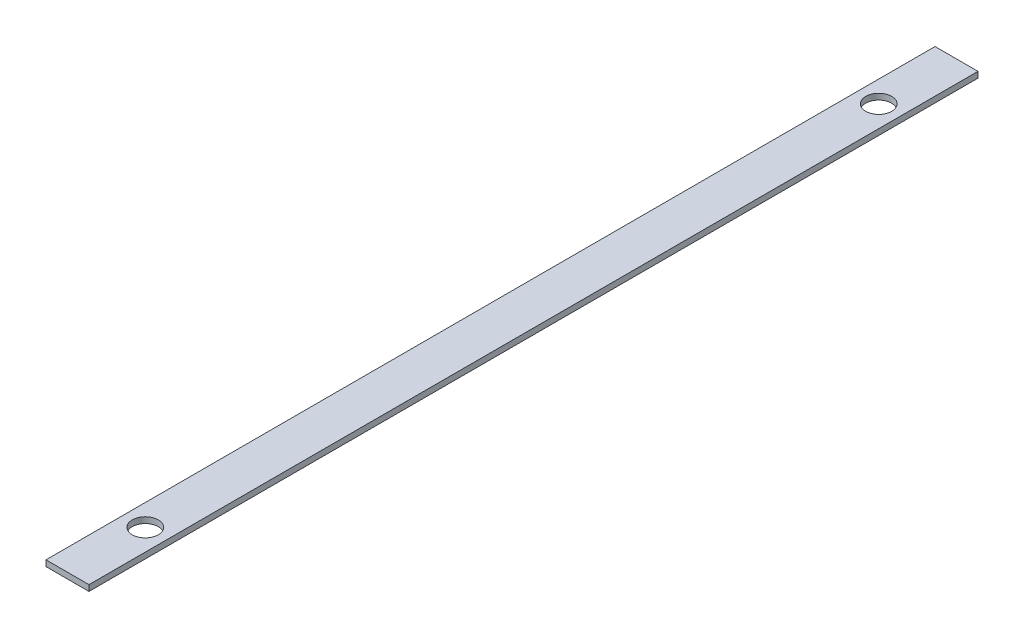
SolidWorks part; units mm, degrees
ref_plane "Front Plane" through (0, 0, 0) normal (0, 0, 1) x (1, 0, 0)
ref_plane "Top Plane" through (0, 0, 0) normal (0, 1, 0) x (1, 0, 0)
ref_plane "Right Plane" through (0, 0, 0) normal (1, 0, 0) x (0, 0, -1)
sketch "Sketch1" plane through (0, 0, 0) normal (0, 0, 1) x (1, 0, 0)
  line L1 (-2.9, -0.4) -> (2.9, -0.4)
  line L2 (-2.9, -0.4) -> (-2.9, 0.4)
  line L3 (-2.9, 0.4) -> (2.9, 0.4)
  line L4 (2.9, -0.4) -> (2.9, 0.4)
  point P4 (0, 0.4)
  point P6 (2.9, 0)
  dimension "D1" = 0.8
  dimension "D2" = 5.8
extrude "Boss-Extrude1" add sketch "Sketch1" along normal mid plane 120
sketch "Sketch3" plane through (0, 0.4, 0) normal (0, 1, 0) x (1, 0, 0)
  line L0 (2.9, -60) -> (-2.9, -60) construction
  line L1 (-2.9, 0) -> (2.9, 0) construction
  line L2 (-2.9, -60) -> (-2.9, 60) construction
  line L3 (2.9, -60) -> (2.9, 60) construction
  circle A0 centre (0, -49.5) radius 1.75
  circle A1 centre (0, 49.5) radius 1.75
  point P5 (0, -60)
  dimension "D1" = 3.5
  dimension "D2" = 10.5
extrude "Cut-Extrude1" cut sketch "Sketch3" against normal up to surface (0.8 mm away) up to face at (0, -0.4, 0)
